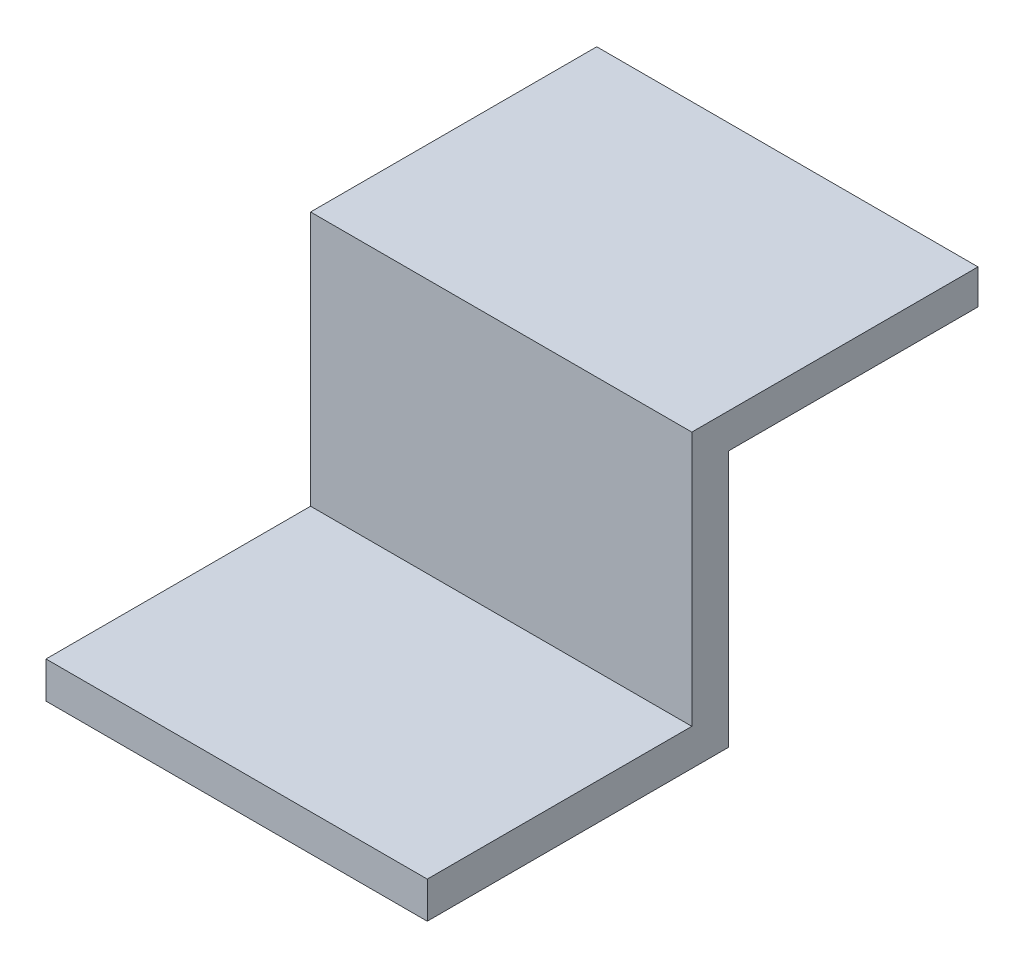
SolidWorks part; units mm, degrees
ref_plane "Front Plane" through (0, 0, 0) normal (0, 0, 1) x (1, 0, 0)
ref_plane "Top Plane" through (0, 0, 0) normal (0, 1, 0) x (1, 0, 0)
ref_plane "Right Plane" through (0, 0, 0) normal (1, 0, 0) x (0, 0, -1)
sketch "Sketch10" plane through (0, 0, 0) normal (1, 0, 0) x (0, 0, -1)
  line L0 (52.3533, 44.6272) -> (52.3533, 0)
  line L1 (52.3533, 0) -> (0, 0)
  line L2 (0, 0) -> (0, 6.35)
  line L3 (0, 6.35) -> (46.0033, 6.35)
  line L4 (46.0033, 6.35) -> (46.0033, 50.6588)
  line L5 (46.0033, 50.6588) -> (52.3533, 50.6588)
  line L7 (52.3533, 50.6588) -> (95.7628, 50.6588)
  line L9 (52.3533, 44.6272) -> (95.7628, 44.6272)
  line L10 (95.7628, 50.6588) -> (95.7628, 44.6272)
extrude "Extrude4" add sketch "Sketch10" against normal blind 66.294
ref_plane "Plane3" through (0, 3.2941, 3.1728) normal (0, -0.7202, -0.6937) x (1, 0, 0)
sketch "Sketch11" plane through (0, 3.2941, 3.1728) normal (0, -0.7202, -0.6937) x (1, 0, 0)
  line L0 (-66.294, -68.2766) -> (-66.294, -4.4051)
